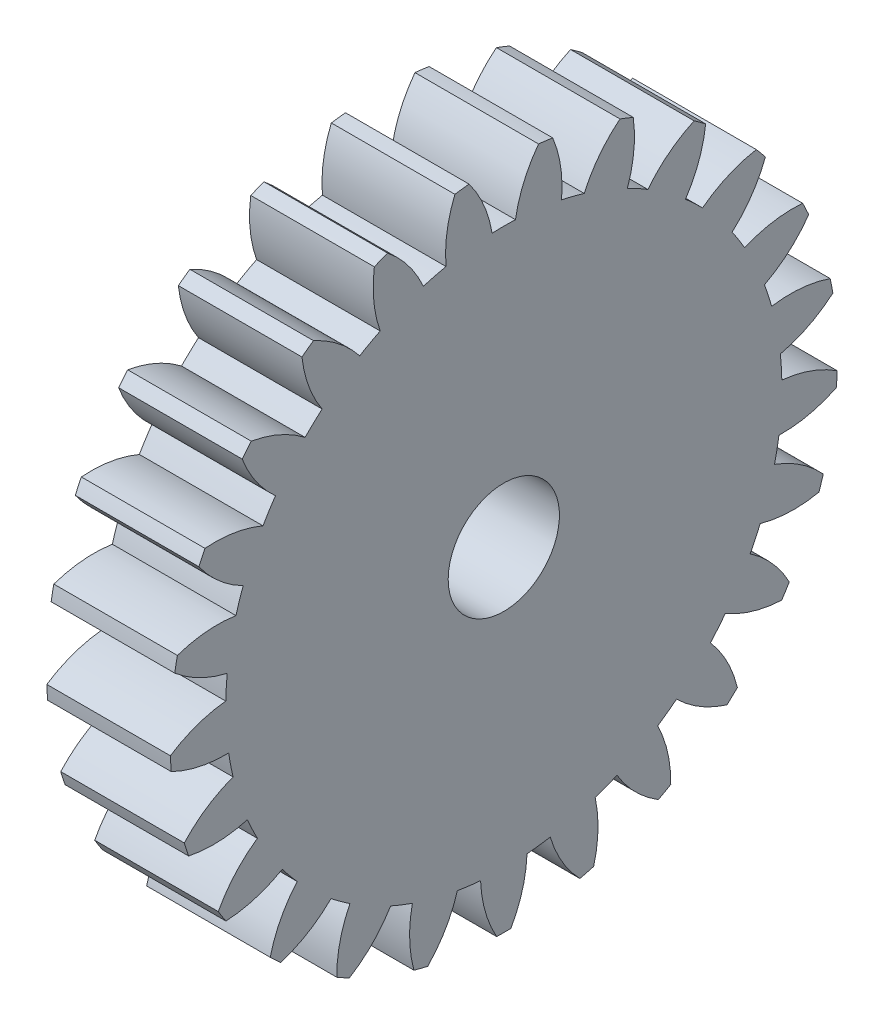
SolidWorks part; units mm, degrees
ref_plane "Plane1" through (0, 0, 0) normal (0, 0, 1) x (1, 0, 0)
ref_plane "Plane2" through (0, 0, 0) normal (0, 1, 0) x (1, 0, 0)
ref_plane "Plane3" through (0, 0, 0) normal (1, 0, 0) x (0, 0, -1)
other "Configuration Table"
sketch "HoldingSke" plane through (0, 0, 0) normal (0, 1, 0) x (1, 0, 0)
  line L0 (0, 0) -> (0.4532, -0.2113)
  line L1 (-15, 0) -> (100, 0) construction
  line L2 (0, 0) -> (-2.1039, 2.3779)
  line L3 (0, 0) -> (-11.863, 4.5341)
  line L4 (0, 0) -> (7.8269, 3.6497)
  line L5 (0, 0) -> (-46.8476, -17.4728)
  line L6 (0, 0) -> (-8.2896, -5.593)
  line L7 (-2.1039, 2.3779) -> (8.6586, 51.2059)
  line L8 (-76.2, 54.61) -> (-74.8, 54.61)
  line L9 (-71.009, 38.7566) -> (-53.1078, 45.2721)
  line L10 (-76.2, 71.12) -> (104.1128, 71.12)
  line L11 (0, 0) -> (-10, 0)
  line L12 (-76.2, 101.6) -> (-76.133, 101.6)
  line L13 (24.9733, 27.94) -> (52.9518, 28.4284)
  line L14 (24.9733, 27.94) -> (24.9743, 27.94)
  line L15 (24.9733, 27.94) -> (100.4006, 29.5858)
  line L16 (-63.627, -2) -> (-12.827, -2)
  circle A0 centre (0, 0) radius 4.5
  circle A1 centre (0, 0) radius 22.499
  circle A2 centre (0, 0) radius 37.5
  circle A3 centre (0, 0) radius 4.5
  dimension "MHD" = 44.998
  dimension "Hub_dia" = 75
  dimension "Bore" = 9
  dimension "MBD" = 9
  dimension "Num_teeth" = 25
  dimension "Pitch" = 0.5
  dimension "Overall_len" = 50
  dimension "Show_teeth" = 25
  dimension "Thickness" = 10
  dimension "OAL" = 50.0001
  dimension "T_dim" = 1.4
  dimension "Ap" = 20
  dimension "H" = 19.05
  dimension "Pitch_radius" = 180.3128
  dimension "Width" = 10
  dimension "Backlash" = 0.067
  dimension "Addendum_fac" = 1
  dimension "Dedendum_fac" = 1.25
  dimension "Clearance_fac" = 0.25
  dimension "Dedendum_add" = 0.001
  dimension "Module" = 2
sketch "BasProSke" plane through (0, 0, 0) normal (0, 1, 0) x (1, 0, 0)
  line L0 (-10, 0) -> (60, 0) construction
  line L1 (0, 0) -> (0, 27)
  line L2 (0, 0) -> (10, 0)
  line L3 (10, 0) -> (10, 27)
  line L4 (10, 27) -> (0, 27)
  dimension "Thickness" = 10
  dimension "Diameter" = 54
revolve "Base-Revolve" add sketch "BasProSke" angle 360 about L0
sketch "TooCutSke" plane through (0, 0, 0) normal (1, 0, 0) x (0, 0, -1)
  line L1 (0, 0) -> (0, 107) construction
  line L2 (0, 0) -> (-1.687, 24.943) construction
  line L3 (0, 0) -> (-6.2561, 49.5219) construction
  line L4 (-1.687, 24.943) -> (-3.128, 24.761) construction
  arc A0 (0.9462, 22.4791) -> (-0.9462, 22.4791) centre (0, 0) ccw
  arc A1 (2.8295, 26.8769) -> (-2.8295, 26.8769) centre (0, 0) ccw
  circle A2 centre (0, 0) radius 25 construction
  circle A3 centre (0, 0) radius 23.4923 construction
  arc A4 (-0.9462, 22.4791) -> (-2.8295, 26.8769) centre (-10.8135, 20.8556) ccw
  arc A5 (2.8295, 26.8769) -> (0.9462, 22.4791) centre (10.8135, 20.8556) ccw
  dimension "Root_dia" = 44.998
  dimension "Overcut_dia" = 54.0508
  dimension "Pitch_dia" = 50
  dimension "Base_dia" = 46.9846
  dimension "Flank_rad" = 10
  dimension "Half_ang" = 7.2
  dimension "Half_CT" = 1.4525
extrude "ToothCut" cut sketch "TooCutSke" along normal through all
fillet "Breaks" [suppressed] radius 0.04
fillet "RootFillets" [suppressed] radius 0.501
pattern_circular "TeethCuts" count 25 every 14.4 about axis through (-10, 0, 0) along (1, 0, 0) of "ToothCut", "RootFillets", "Breaks"
sketch "HubNeaOneSke" plane through (0, 0, 0) normal (-1, 0, 0) x (0, 0, 1)
  circle A0 centre (0, 0) radius 22.499
  dimension "Diameter" = 44.998
extrude "HubNearOne" [suppressed] add sketch "HubNeaOneSke" along normal blind 40.0001
sketch "HubNeaBotSke" plane through (0, 0, 0) normal (-1, 0, 0) x (0, 0, 1)
  circle A0 centre (0, 0) radius 22.499
  dimension "Diameter" = 44.998
extrude "HubNearBoth" [suppressed] add sketch "HubNeaBotSke" along normal blind 20
ref_plane "FarPln" through (10, 0, 0) normal (1, 0, 0) x (0, 0, -1)
sketch "HubFarSke" plane through (10, 0, 0) normal (1, 0, 0) x (0, 0, -1)
  circle A0 centre (0, 0) radius 22.499
  dimension "Diameter" = 44.998
extrude "HubFar" [suppressed] add sketch "HubFarSke" along normal blind 20
sketch "BorSke" plane through (0, 0, 0) normal (1, 0, 0) x (0, 0, -1)
  circle A0 centre (0, 0) radius 4.5
  dimension "Diameter" = 9
extrude "Bore" cut sketch "BorSke" along normal mid plane 100.0001
sketch "KeySke" plane through (0, 0, 0) normal (1, 0, 0) x (0, 0, -1)
  line L0 (-1.5, 0) -> (-1.5, 5.9)
  line L1 (-1.5, 5.9) -> (1.5, 5.9)
  line L2 (1.5, 5.9) -> (1.5, 0)
  line L3 (0, 0) -> (0, 34) construction
  line L4 (-1.5, 0) -> (1.5, 0)
  dimension "Offset" = 5.9
  dimension "Width" = 3
extrude "Keyway" [suppressed] cut sketch "KeySke" along normal mid plane 100.0001
pattern_circular "Keyway2" [suppressed] count 2 every 90 about axis through (-10, 0, 0) along (1, 0, 0)
equation "' \"Module@HoldingSke\" = 6.35"
equation "' \"Num_teeth@HoldingSke\" = 12"
equation "' \"Ap@HoldingSke\" =  20"
equation "' \"Ap@HoldingSke\" = 20"
equation "' \"Width@HoldingSke\" = 0.5 * 25.4"
equation "' \"Hub_dia@HoldingSke\"= 1 * 25.4"
equation "' \"Hub_dia@HoldingSke\" = 1 * 25.4"
equation "' \"Overall_len@HoldingSke\" = 1.0 * 25.4"
equation "' \"Bore@HoldingSke\" = 0.75 * 25.4"
equation "' \"T_dim@HoldingSke\" = 0.1 * 25.4"
equation "' \"Width@KeySke\" = 0.25 * 25.4"
equation "' \"Show_teeth@HoldingSke\" = 13"
equation "' \"Backlash@HoldingSke\" = 0.009 * 25.4"
equation "' \"Addendum_fac@HoldingSke\" = 1.0"
equation "' \"Dedendum_fac@HoldingSke\" = 1.25"
equation "' \"Dedendum_add@HoldingSke\" = 0.00005 * 25.4"
equation "' \"Clearance_fac@HoldingSke\" = 0.25"
equation "\"Pitch@HoldingSke\" = 1 / \"Module@HoldingSke\""
equation "\"Overcut_dia@TooCutSke\" = (\"Num_teeth@HoldingSke\" + 2 * \"Addendum_fac@HoldingSke\") / \"Pitch@HoldingSke\" + 0.002 * 25.4"
equation "\"Pitch_dia@TooCutSke\" = \"Num_teeth@HoldingSke\" / \"Pitch@HoldingSke\""
equation "\"Base_dia@TooCutSke\" = \"Num_teeth@HoldingSke\" / \"Pitch@HoldingSke\" * cos((\"Ap@HoldingSke\"  * 3.14159265 / 180))"
equation "\"Root_dia@TooCutSke\" = (\"Num_teeth@HoldingSke\" + 2) / \"Pitch@HoldingSke\" - 2 * (\"Addendum_fac@HoldingSke\" + \"Dedendum_fac@HoldingSke\") / \"Pitch@HoldingSke\" - \"Dedendum_add@HoldingSke\" * 2"
equation "\"Half_ang@TooCutSke\" = 180 / \"Num_teeth@HoldingSke\""
equation "\"Half_CT@TooCutSke\" = \"Num_teeth@HoldingSke\" / \"Pitch@HoldingSke\" * sin((3.14159265 / 2 / \"Num_teeth@HoldingSke\")) / 2 - 7 * \"Backlash@HoldingSke\" / 4"
equation "\"Flank_rad@TooCutSke\" = \"Num_teeth@HoldingSke\" / \"Pitch@HoldingSke\" / 5"
equation "\"Radius@RootFillets\" = \"Clearance_fac@HoldingSke\" / \"Pitch@HoldingSke\" + \"Dedendum_add@HoldingSke\""
equation "\"Break_rad@Breaks\" = 0.02 / \"Pitch@HoldingSke\""
equation "\"Thickness@HoldingSke\" = \"Width@HoldingSke\""
equation "\"OAL@HoldingSke\" = \"Thickness@HoldingSke\""
equation "\"MHD@HoldingSke\" = (\"Num_teeth@HoldingSke\" + 2) / \"Pitch@HoldingSke\" - 2 * (\"Addendum_fac@HoldingSke\" + \"Dedendum_fac@HoldingSke\")  / \"Pitch@HoldingSke\" - \"Dedendum_add@HoldingSke\" * 2"
equation "\"MBD@HoldingSke\" = (\"Num_teeth@HoldingSke\" + 2) / \"Pitch@HoldingSke\" - 2 * (\"Addendum_fac@HoldingSke\" + \"Dedendum_fac@HoldingSke\")  / \"Pitch@HoldingSke\" - \"Dedendum_add@HoldingSke\" * 2 - 0.002 * 25.4"
equation "\"MHD@HoldingSke\" = ((sgn( \"MHD@HoldingSke\" - \"Hub_dia@HoldingSke\" )-1)*( \"MHD@HoldingSke\" - \"Hub_dia@HoldingSke\" ))/-2+ \"Hub_dia@HoldingSke\""
equation "\"MBD@HoldingSke\" = ((sgn( \"MBD@HoldingSke\" - \"Bore@HoldingSke\" )-1)*( \"MBD@HoldingSke\" - \"Bore@HoldingSke\" ))/-2+ \"Bore@HoldingSke\""
equation "\"OAL@HoldingSke\" = ((sgn( \"OAL@HoldingSke\" - \"Overall_len@HoldingSke\" )+1)*( \"OAL@HoldingSke\" - \"Overall_len@HoldingSke\" ))/2 + \"Overall_len@HoldingSke\" + 0.000002 * 25.4"
equation "\"Num_teeth@TeethCuts\" = int( \"Show_teeth@HoldingSke\" ) + 1"
equation "\"Num_teeth@TeethCuts\" = ((sgn( \"Num_teeth@TeethCuts\" - \"Num_teeth@HoldingSke\" )-1)*( \"Num_teeth@TeethCuts\" - \"Num_teeth@HoldingSke\" ))/-2+ \"Num_teeth@HoldingSke\""
equation "\"Num_teeth@TeethCuts\" = ((sgn( \"Num_teeth@TeethCuts\" - 2.0)+1)*( \"Num_teeth@TeethCuts\" - 2.0))/2 +2.0"
equation "\"Angle@TeethCuts\" = 360.0 / \"Num_teeth@HoldingSke\""
equation "\"Diameter@BasProSke\" = (\"Num_teeth@HoldingSke\" + 2 * \"Addendum_fac@HoldingSke\") / \"Pitch@HoldingSke\""
equation "\"Thickness@BasProSke\"  = \"Thickness@HoldingSke\""
equation "' \"Fillet_rad@BasProSke\" =  \"Thickness@HoldingSke\" * 0.05"
equation "' \"Fillet_rad@BasProSke\" = \"Thickness@HoldingSke\" * 0.05"
equation "\"MHD@HoldingSke\" = ((sgn( \"MHD@HoldingSke\" - \"Root_dia@TooCutSke\" )-1)*( \"MHD@HoldingSke\" - \"Root_dia@TooCutSke\" ))/-2+ \"Root_dia@TooCutSke\""
equation "\"Diameter@HubNeaOneSke\" = \"MHD@HoldingSke\""
equation "\"Length@HubNearOne\" = \"OAL@HoldingSke\" - \"Thickness@BasProSke\""
equation "\"Diameter@HubNeaBotSke\" = \"MHD@HoldingSke\""
equation "\"Length@HubNearBoth\" = ( \"OAL@HoldingSke\" - \"Thickness@BasProSke\" ) / 2.0"
equation "\"Thickness@FarPln\" = \"Thickness@BasProSke\""
equation "\"Diameter@HubFarSke\" = \"MHD@HoldingSke\""
equation "\"Length@HubFar\" = ( \"OAL@HoldingSke\" - \"Thickness@BasProSke\" ) / 2.0"
equation "\"Diameter@BorSke\" = \"MBD@HoldingSke\""
equation "\"D1@Bore\" = \"OAL@HoldingSke\" * 2.0"
equation "\"D1@Keyway\" = \"OAL@HoldingSke\" * 2.0"
equation "\"Offset@KeySke\" = \"T_dim@HoldingSke\" + \"MBD@HoldingSke\" / 2.0"
